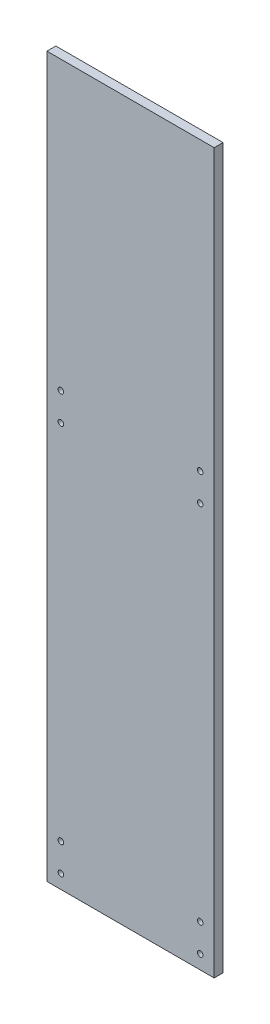
SolidWorks part; units mm, degrees
ref_plane "Front Plane" through (0, 0, 0) normal (0, 0, 1) x (1, 0, 0)
ref_plane "Top Plane" through (0, 0, 0) normal (0, 1, 0) x (1, 0, 0)
ref_plane "Right Plane" through (0, 0, 0) normal (1, 0, 0) x (0, 0, -1)
sketch "Model" plane through (0, 0, 0) normal (0, 0, 1) x (1, 0, 0)
  line L0 (189.8791, -1) -> (159.8791, -1)
  line L1 (159.8791, -1) -> (159.8791, 128)
  line L2 (189.8791, 128) -> (189.8791, -1)
  line L3 (159.8791, 128) -> (189.8791, 128)
  circle A0 centre (162.3791, 6.5) radius 0.5
  circle A1 centre (162.3791, 71.5) radius 0.5
  circle A2 centre (187.3791, 6.5) radius 0.5
  circle A3 centre (187.3791, 71.5) radius 0.5
  circle A4 centre (162.3791, 76.5) radius 0.5
  circle A5 centre (187.3791, 76.5) radius 0.5
  circle A6 centre (162.3791, 1.5) radius 0.5
  circle A7 centre (187.3791, 1.5) radius 0.5
extrude "Boss-Extrude1" add sketch "Model" along normal blind 1.6
